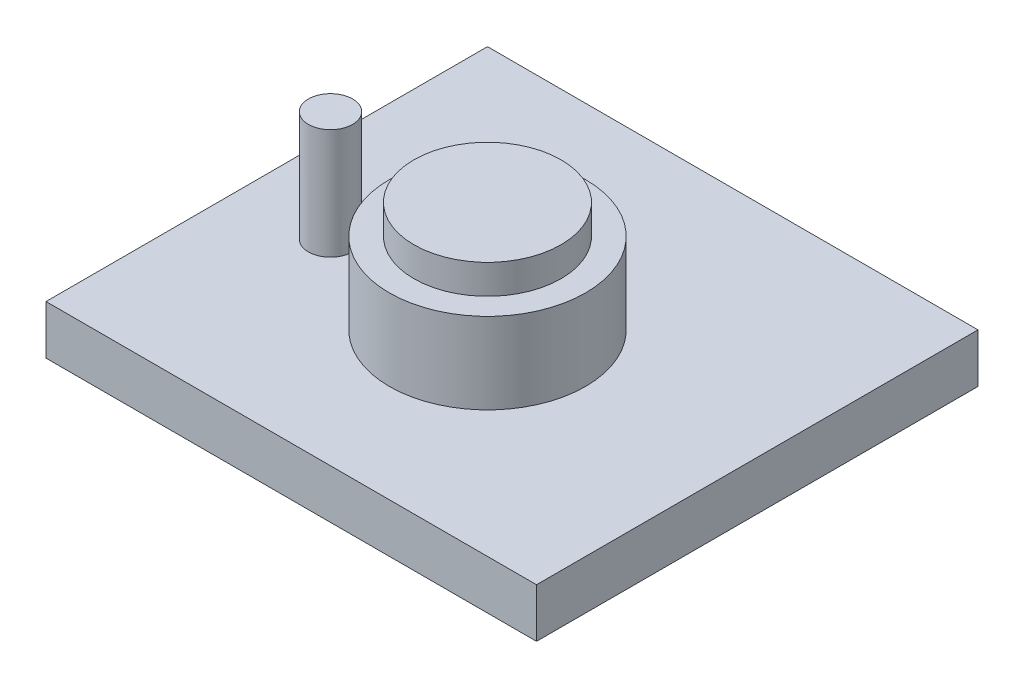
SolidWorks part; units mm, degrees
ref_plane "Front Plane" through (0, 0, 0) normal (0, 0, 1) x (1, 0, 0)
ref_plane "Top Plane" through (0, 0, 0) normal (0, 1, 0) x (1, 0, 0)
ref_plane "Right Plane" through (0, 0, 0) normal (1, 0, 0) x (0, 0, -1)
sketch "Sketch3" plane through (0, 0, 0) normal (0, 0, 1) x (1, 0, 0)
  line L0 (0, 0) -> (10, 0)
  line L1 (10, 0) -> (10, 8.26)
  line L2 (10, 8.26) -> (7.5, 8.26)
  line L3 (7.5, 8.26) -> (7.5, 11.26)
  line L4 (7.5, 11.26) -> (0, 11.26)
  line L5 (0, 11.26) -> (0, 0)
  dimension "D1" = 10
  dimension "D2" = 7.5
  dimension "D3" = 3
  dimension "D4" = 8.26
revolve "Revolve1" add sketch "Sketch3" angle 360 about L5
sketch "Sketch4" plane through (0, 0, 0) normal (0, -1, 0) x (1, 0, 0)
  line L1 (-25, 20) -> (25, 20)
  line L2 (-25, 20) -> (-25, -20)
  line L3 (-25, -20) -> (25, -20)
  line L4 (25, 20) -> (25, -20)
  line L5 (-25, 20) -> (25, -20) construction
  line L6 (-25, -20) -> (25, 20) construction
  point P1 (0, 0)
  dimension "D1" = 40
  dimension "D2" = 50
extrude "Boss-Extrude1" add sketch "Sketch4" along normal blind 5
sketch "Sketch5" plane through (0, 0, 0) normal (0, 1, 0) x (1, 0, 0)
  line L1 (0, 0) -> (-16, 0) construction
  circle A0 centre (-16, 0) radius 2.25
  dimension "D2" = 4.5
  dimension "D1" = 16
extrude "Boss-Extrude2" add sketch "Sketch5" along normal blind 11.26
sketch "Sketch6" plane through (0, 0, -20) normal (0, 0, -1) x (-1, 0, 0)
  line L1 (25, -5) -> (-25, -5)
  line L2 (25, -5) -> (25, 0)
  line L3 (25, 0) -> (-25, 0)
  line L4 (-25, -5) -> (-25, 0)
extrude "Boss-Extrude3" add sketch "Sketch6" along normal blind 5
